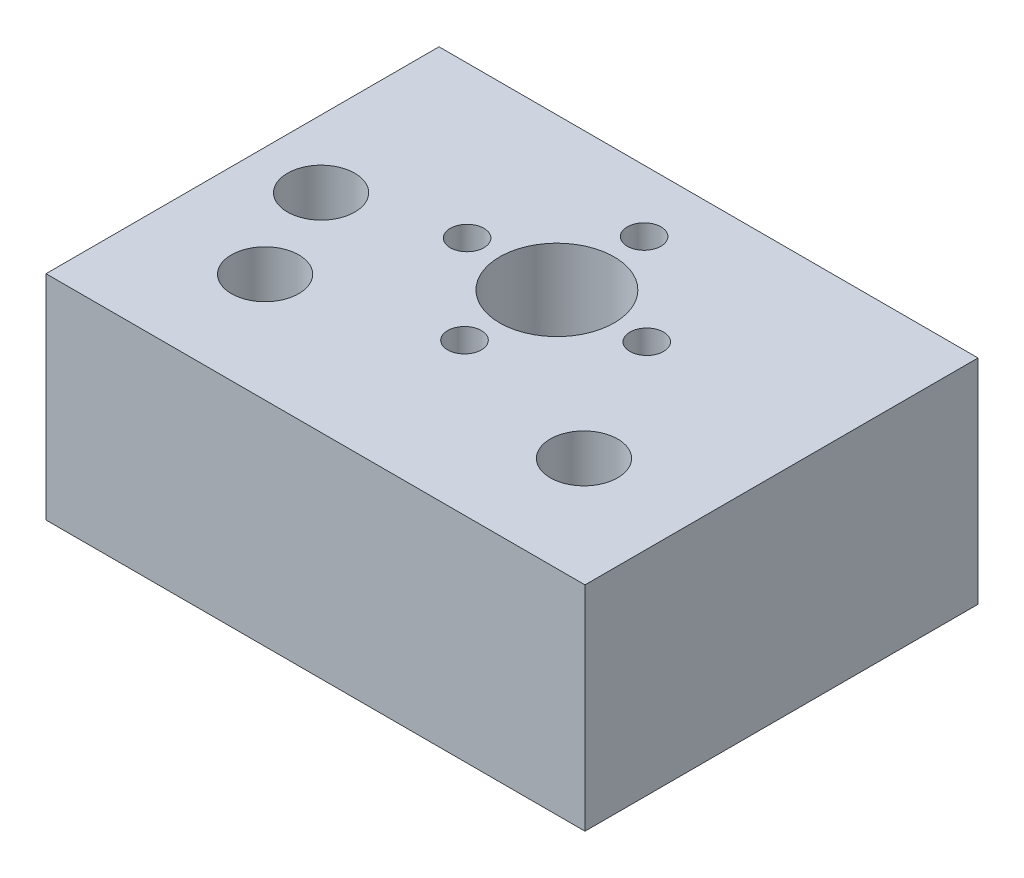
SolidWorks part; units mm, degrees
ref_plane "Plano frontal" through (0, 0, 0) normal (0, 0, 1) x (1, 0, 0)
ref_plane "Plano superior" through (0, 0, 0) normal (0, 1, 0) x (1, 0, 0)
ref_plane "Plano direito" through (0, 0, 0) normal (1, 0, 0) x (0, 0, -1)
sketch "Esboço1" plane through (0, 0, 0) normal (0, 1, 0) x (1, 0, 0)
  line L1 (0, 0) -> (48, 0)
  line L2 (0, 0) -> (0, 35)
  line L3 (0, 35) -> (48, 35)
  line L4 (48, 0) -> (48, 35)
  dimension "D1" = 48
  dimension "D2" = 35
extrude "Ressalto-extrusão1" add sketch "Esboço1" along normal blind 19
sketch "Esboço4" plane through (0, 19, 0) normal (0, 1, 0) x (1, 0, 0)
  line L0 (48, 35) -> (0, 35) construction
  circle A0 centre (24, 21.5) radius 5.1
  dimension "D2" = 10.2
  dimension "D1" = 13.5
extrude "Corte-extrusão3" cut sketch "Esboço4" against normal blind 25
sketch "Esboço6" plane through (0, 19, 0) normal (0, 1, 0) x (1, 0, 0)
  circle A0 centre (23.7676, 29.4966) radius 1.5
  circle A1 centre (16, 21.5) radius 1.5
  circle A2 centre (32, 21.5) radius 1.5
  circle A3 centre (23.7676, 13.5034) radius 1.5
  dimension "D5" = 3
  dimension "D6" = 3
  dimension "D7" = 3
  dimension "D8" = 3
sketch "Esboço7" plane through (0, 19, 0) normal (0, 1, 0) x (1, 0, 0)
  circle A0 centre (9.8, 9.71) radius 3
  circle A1 centre (38.2, 9.71) radius 3
  dimension "D5" = 6
  dimension "D6" = 6
extrude "Corte-extrusão7" cut sketch "Esboço7" against normal through all contours A0 | A1
sketch "Esboço8" plane through (0, 0, 0) normal (0, -1, 0) x (1, 0, 0)
  line L0 (48, -35) -> (0, -35) construction
  line L1 (0, -35) -> (0, 0) construction
  circle A0 centre (6, -18.5) radius 3
  dimension "D3" = 6
  dimension "D1" = 16.5
  dimension "D2" = 6
extrude "Corte-extrusão8" cut sketch "Esboço8" against normal through all
sketch "Esboço9" plane through (0, 0, -35) normal (0, 0, -1) x (-1, 0, 0)
  line L0 (0, 19) -> (0, 0) construction
  circle A1 centre (-6, 9.5) radius 2
  dimension "D2" = 4
  dimension "D1" = 6
extrude "Corte-extrusão9" cut sketch "Esboço9" against normal blind 17
extrude "Corte-extrusão10" cut sketch "Esboço6" along direction (0, -1, 0) on the side against the normal blind 10
